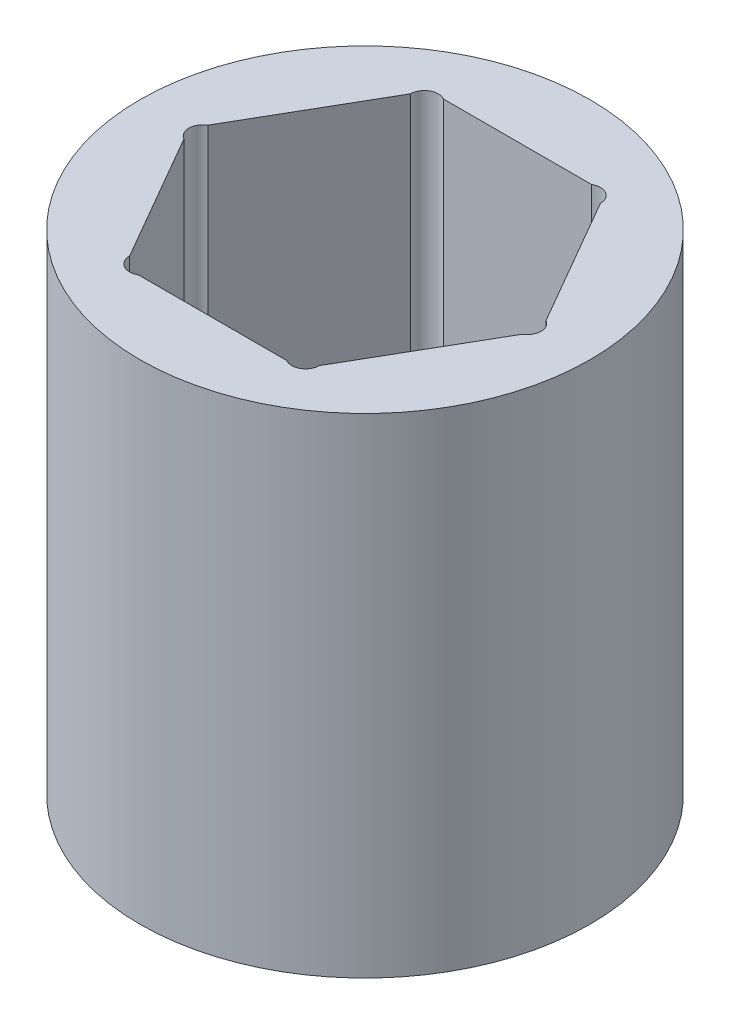
SolidWorks part; units mm, degrees
ref_plane "Front Plane" through (0, 0, 0) normal (0, 0, 1) x (1, 0, 0)
ref_plane "Top Plane" through (0, 0, 0) normal (0, 1, 0) x (1, 0, 0)
ref_plane "Right Plane" through (0, 0, 0) normal (1, 0, 0) x (0, 0, -1)
sketch "Sketch1" plane through (0, 0, 0) normal (0, 1, 0) x (1, 0, 0)
  line L0 (0, 0) -> (3.8128, 6.604) construction
  line L1 (7.6256, 0) -> (3.8128, 6.604)
  line L2 (3.8128, 6.604) -> (-3.8128, 6.604)
  line L3 (-3.8128, 6.604) -> (-7.6256, 0)
  line L4 (-7.6256, 0) -> (-3.8128, -6.604)
  line L5 (-3.8128, -6.604) -> (3.8128, -6.604)
  line L6 (3.8128, -6.604) -> (7.6256, 0)
  circle A0 centre (0, 0) radius 6.604 construction
  circle A1 centre (0, 0) radius 9.7536
  circle A2 centre (3.5128, 6.0844) radius 0.6
  circle A3 centre (7.0256, 0) radius 0.6
  circle A4 centre (3.5128, -6.0844) radius 0.6
  circle A5 centre (-3.5128, -6.0844) radius 0.6
  circle A6 centre (-7.0256, 0) radius 0.6
  circle A7 centre (-3.5128, 6.0844) radius 0.6
  point P25 (0, 0)
  dimension "D1" = 13.208
  dimension "D2" = 19.5072
  dimension "D3" = 1.2
  dimension "D4" = 6
extrude "Boss-Extrude1" add sketch "Sketch1" along normal blind 21.1836 contours A1 A7 L2 A2 L1 A3 L6 A4 L5 A5 L4 A6 L3
